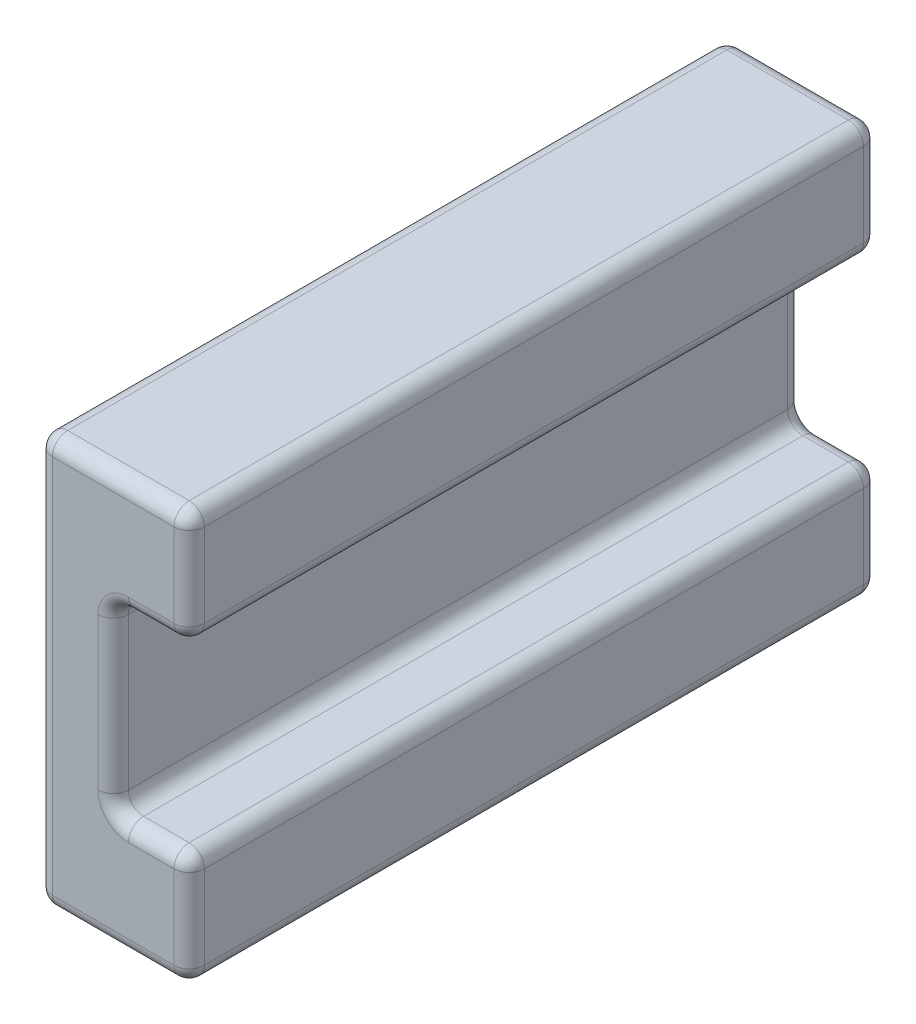
SolidWorks part; units mm, degrees
ref_plane "Front Plane" through (0, 0, 0) normal (0, 0, 1) x (1, 0, 0)
ref_plane "Top Plane" through (0, 0, 0) normal (0, 1, 0) x (1, 0, 0)
ref_plane "Right Plane" through (0, 0, 0) normal (1, 0, 0) x (0, 0, -1)
sketch "Sketch1" plane through (0, 0, 0) normal (0, 0, 1) x (1, 0, 0)
  line L0 (5, -6) -> (5, -13.5)
  line L1 (-5, 13.5) -> (5, 13.5)
  line L2 (-5, 13.5) -> (-5, -13.5)
  line L3 (-5, -13.5) -> (5, -13.5)
  line L4 (5, 13.5) -> (5, 6)
  line L5 (-5, 13.5) -> (5, -13.5) construction
  line L6 (-5, -13.5) -> (5, 13.5) construction
  line L7 (0, -6) -> (5, -6)
  line L8 (0, -6) -> (0, 6)
  line L9 (0, 6) -> (5, 6)
  line L11 (0, -6) -> (5, 0) construction
  line L12 (0, 6) -> (5, 0) construction
  point P0 (0, 0)
  point P6 (5, 0)
  dimension "D1" = 27
  dimension "D2" = 10
  dimension "D3" = 12
  dimension "D4" = 5
extrude "Boss-Extrude1" add sketch "Sketch1" along normal blind 45.4
sketch "Sketch3" plane through (-5, 0, 0) normal (-1, 0, 0) x (0, 0, 1)
  line L0 (0, 0) -> (5.5023, 0) construction
  line L1 (17.35, 15.8594) -> (17.35, 13.4331) construction
  circle A0 centre (9.85, 10) radius 1.7
  circle A1 centre (24.85, 10) radius 1.7
  circle A2 centre (24.85, -10) radius 1.7
  circle A3 centre (9.85, -10) radius 1.7
  dimension "D1" = 3.4
  dimension "D2" = 15
  dimension "D3" = 20
fillet "Fillet1" radius 1 24 edges at (-5, -13.5, 22.7) (2.5, -6, 0) (2.5, 6, 0) (-5, 0, 0) (0, -13.5, 0) (-5, 0, 45.4) (2.5, 6, 45.4) (2.5, -6, 45.4) (0, -13.5, 45.4) (0, -6, 22.7) (0, 0, 45.4) (0, 6, 22.7) (0, 0, 0) (5, -13.5, 22.7) (5, -9.75, 45.4) (5, -6, 22.7) (5, -9.75, 0) (5, 6, 22.7) (5, 9.75, 45.4) (5, 9.75, 0) (5, 13.5, 22.7) (0, 13.5, 45.4) (-5, 13.5, 22.7) (0, 13.5, 0)
hole_wizard "M3 Tapped Hole2" positions "3DSketch2" profile "Sketch5" tap size "M3" standard "ISO"
sketch3d "3DSketch2"
  line L0 (-5, 0, 1) -> (-5, 0, 44.4) construction
  line L6 (-5, 10, 12.7) -> (-5, -10, 12.7)
  line L7 (-5, 10, 12.7) -> (-5, 10, 32.7)
  line L8 (-5, 10, 32.7) -> (-5, -10, 32.7)
  line L9 (-5, -10, 12.7) -> (-5, -10, 32.7)
  line L10 (-5, 10, 12.7) -> (-5, -10, 32.7) construction
  line L11 (-5, 10, 32.7) -> (-5, -10, 12.7) construction
  point P20 (-5, 10, 12.7)
  point P22 (-5, 10, 32.7)
  point P24 (-5, -10, 32.7)
  point P26 (-5, -10, 12.7)
  point P180 (-5, 0, 22.7)
  point P246 (0, 0, 0)
  point P247 (-5, 10, 12.7)
  point P248 (-5, 10, 32.7)
  point P249 (-5, -10, 32.7)
  point P250 (-5, -10, 12.7)
sketch "Sketch5" plane through (-5, 10, 12.7) normal (0, 1, 0) x (0, 0, 1)
  line L0 (0, 0) -> (0, 5)
  line L1 (0, 5) -> (1.25, 4.2489)
  line L2 (1.25, 4.2489) -> (1.25, 0.275)
  line L3 (1.25, 0.275) -> (1.525, 0)
  line L5 (1.525, 0) -> (0, 0)
  line L6 (-1.25, 0.275) -> (-1.525, 0) construction
  line L10 (0, 5) -> (-1.25, 4.2489) construction
  line L11 (0, -6.35) -> (0, 107.95) construction
  dimension "Tap Drill Dia." = 2.5
  dimension "Tap Drill Depth" = 5
  dimension "Near C'Sink Dia." = 3.05
  dimension "Near C'Sink Angle" = 90
  dimension "Drill Angle" = 118
cosmetic thread "Hole Thread5" parameters "D1"=6, "D2"=3
cosmetic thread "Hole Thread6" parameters "D1"=6, "D2"=3
cosmetic thread "Hole Thread7" parameters "D1"=6, "D2"=3
cosmetic thread "Hole Thread8" parameters "D1"=6, "D2"=3
cosmetic thread "Hole Thread9" parameters "D1"=6, "D2"=3
sketch "Sketch6" plane through (-5, 0, 0) normal (-1, 0, 0) x (0, 0, 1)
  circle A0 centre (12.7, 10) radius 1.75
  circle A1 centre (32.7, 10) radius 1.9
  circle A2 centre (12.7, -10) radius 1.9
  circle A3 centre (32.7, -10) radius 1.9
  point P12 (0, 0)
  point P13 (12.7, 10)
  point P15 (0, 0)
  point P16 (0, 0)
  point P17 (32.7, 10)
  point P19 (0, 0)
  point P20 (12.7, -10)
  point P22 (0, 0)
  point P23 (32.7, -10)
  dimension "D1" = 3.5
  dimension "D2" = 3.8
  dimension "D3" = 3.8
  dimension "D4" = 3.8
